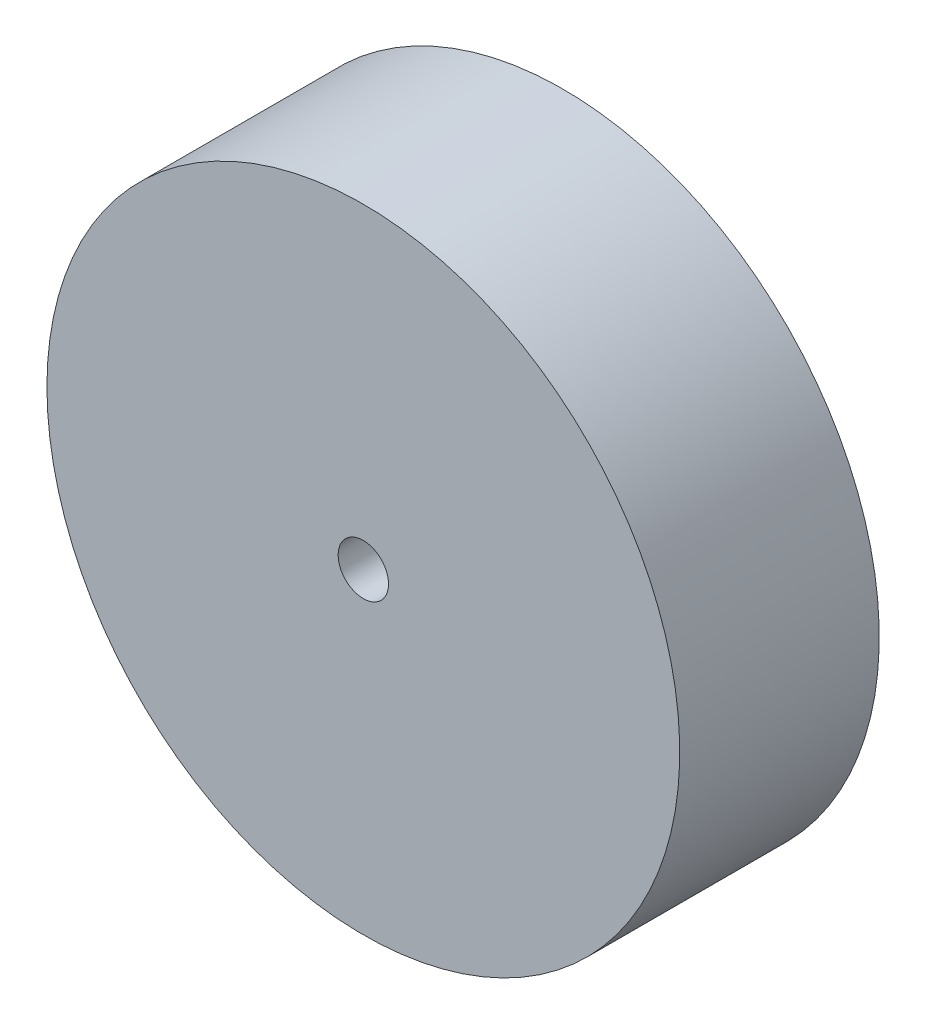
SolidWorks part; units mm, degrees
ref_plane "Front Plane" through (0, 0, 0) normal (0, 0, 1) x (1, 0, 0)
ref_plane "Top Plane" through (0, 0, 0) normal (0, 1, 0) x (1, 0, 0)
ref_plane "Right Plane" through (0, 0, 0) normal (1, 0, 0) x (0, 0, -1)
sketch "Croquis1" plane through (0, 0, 0) normal (0, 0, 1) x (1, 0, 0)
  circle A0 centre (0, 0) radius 31.4
  circle A1 centre (0, 0) radius 2.5
  dimension "D1" = 5
  dimension "D2" = 62.8
extrude "Saliente-Extruir1" add sketch "Croquis1" along normal blind 19.8
